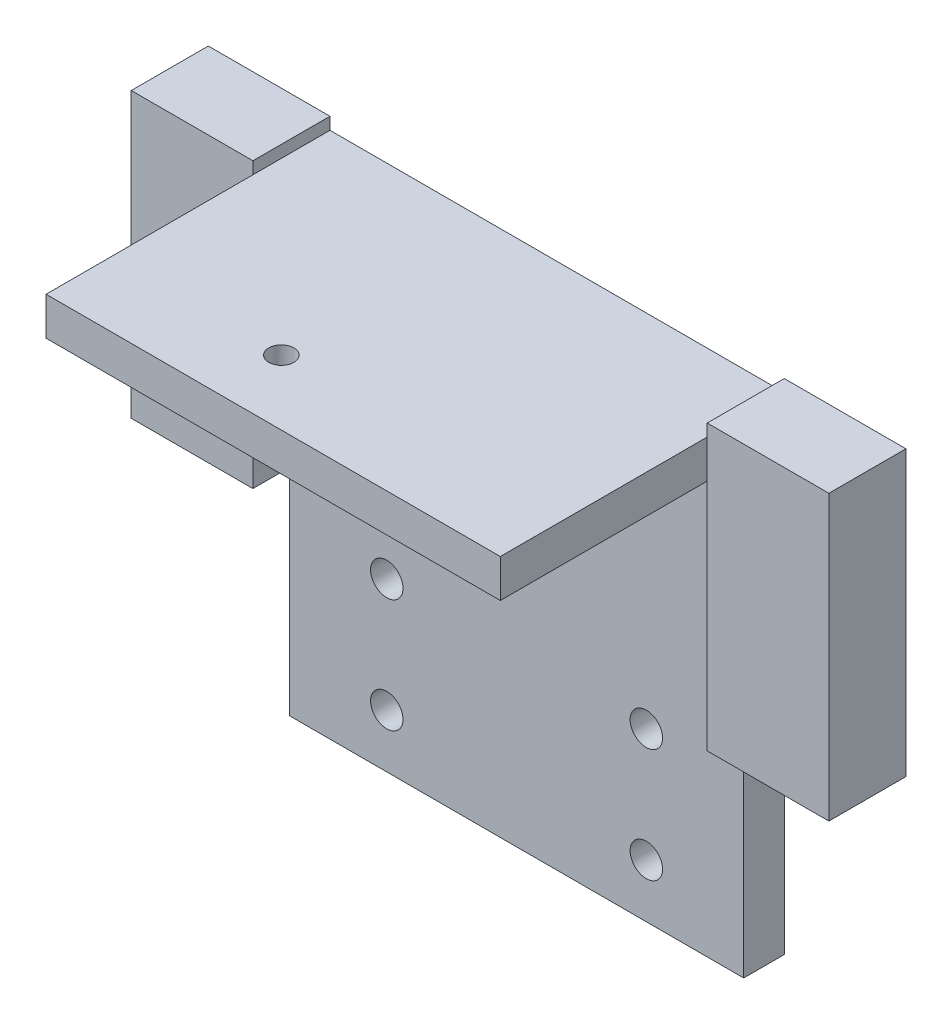
SolidWorks part; units mm, degrees
ref_plane "前视基准面" through (0, 0, 0) normal (0, 0, 1) x (1, 0, 0)
ref_plane "上视基准面" through (0, 0, 0) normal (0, 1, 0) x (1, 0, 0)
ref_plane "右视基准面" through (0, 0, 0) normal (1, 0, 0) x (0, 0, -1)
other "Configuration Table"
sketch "草图1" plane through (0, 0, 0) normal (0, 0, 1) x (1, 0, 0)
  line L1 (-28, -30) -> (28, -30)
  line L2 (-28, -30) -> (-28, 30)
  line L3 (-28, 30) -> (28, 30)
  line L4 (28, -30) -> (28, 30)
  line L5 (-28, -30) -> (28, 30) construction
  line L6 (-28, 30) -> (28, -30) construction
  point P0 (0, 0)
  dimension "D1" = 56
  dimension "D2" = 60
extrude "凸台-拉伸1" add sketch "草图1" along normal blind 5
sketch "草图2" plane through (0, 0, 5) normal (0, 0, 1) x (1, 0, 0)
  line L0 (-16, -23.4) -> (-16, -9.4) construction
  line L1 (-28, -30) -> (28, -30) construction
  line L2 (-28, 30) -> (-28, -30) construction
  circle A0 centre (-16, -23.4) radius 2
  circle A1 centre (-16, -9.4) radius 2
  dimension "D3" = 4
  dimension "D1" = 14
  dimension "D2" = 6.6
  dimension "D4" = 12
extrude "切除-拉伸1" cut sketch "草图2" against normal blind 5
mirror "镜向1" about plane through (0, 0, 0) normal (1, 0, 0) of "切除-拉伸1"
sketch "草图3" plane through (0, 0, 5) normal (0, 0, 1) x (1, 0, 0)
  line L0 (28, -30) -> (28, 30) construction
  line L1 (-28, 30) -> (28, 30)
  line L2 (-28, 30) -> (-28, 25.3)
  line L3 (-28, 25.3) -> (28, 25.3)
  line L4 (28, 30) -> (28, 25.3)
  dimension "D1" = 4.7
extrude "凸台-拉伸2" add sketch "草图3" along normal blind 30
sketch "草图4" plane through (0, 30, 0) normal (0, 1, 0) x (1, 0, 0)
  line L0 (28, 0) -> (-28, 0) construction
  line L1 (-28, -35) -> (-28, 0) construction
  circle A0 centre (-7, -27) radius 1.55
  dimension "D3" = 3.1
  dimension "D1" = 27
  dimension "D2" = 21
extrude "切除-拉伸2" cut sketch "草图4" against normal blind 40
sketch "草图5" plane through (0, 0, 5) normal (0, 0, 1) x (1, 0, 0)
  line L1 (-28, 25.3) -> (-3, 25.3)
  line L2 (-28, 25.3) -> (-28, 1.3)
  line L3 (-28, 1.3) -> (-3, 1.3)
  line L4 (-3, 25.3) -> (-3, 1.3)
  dimension "D1" = 24
  dimension "D2" = 25
extrude "凸台-拉伸3" add sketch "草图5" along normal blind 4.3
sketch "草图6" plane through (-28, 0, 0) normal (-1, 0, 0) x (0, 0, 1)
  line L0 (0, 26.5) -> (0, -3.5)
  line L1 (0, 30) -> (0, -30) construction
  line L8 (0, -3.5) -> (9.5, -3.5)
  line L9 (9.5, -3.5) -> (9.5, 31.5)
  line L10 (9.5, 31.5) -> (0, 31.5)
  line L11 (0, 31.5) -> (0, 26.5)
  point P11 (0, 0)
  dimension "D1" = 30
  dimension "D2" = 35
  dimension "D3" = 9.5
  dimension "D4" = 3.5
extrude "凸台-拉伸4" add sketch "草图6" along normal blind 15
mirror "镜向2" about plane through (0, 0, 0) normal (1, 0, 0) of "凸台-拉伸4"
sketch "草图8" plane through (0, 25.3, 0) normal (0, -1, 0) x (1, 0, 0)
  line L1 (-24.9875, 12.3) -> (24.9875, 12.3) construction
  line L2 (-24.9875, 12.3) -> (-24.9875, 31.3) construction
  line L3 (-24.9875, 31.3) -> (24.9875, 31.3) construction
  line L4 (24.9875, 12.3) -> (24.9875, 31.3) construction
  line L5 (-24.9875, 12.3) -> (24.9875, 31.3) construction
  line L6 (-24.9875, 31.3) -> (24.9875, 12.3) construction
  line L7 (-28, 9.3) -> (-3, 9.3) construction
  line L8 (-28, 35) -> (28, 35) construction
  circle A0 centre (-24.9875, 31.3) radius 1.6
  circle A1 centre (24.9875, 31.3) radius 1.6
  circle A2 centre (24.9875, 12.3) radius 1.6
  circle A3 centre (-24.9875, 12.3) radius 1.6
  point P0 (0, 21.8)
  point P5 (25, 31.3)
  point P6 (0, 21.8)
  point P16 (-24.9875, 31.3)
  dimension "D5" = 3.2
  dimension "D1" = 21.8
  dimension "D2" = 3
  dimension "D4" = 3.7
sketch "草图9" plane through (0, 0, 9.5) normal (0, 0, 1) x (1, 0, 0)
  line L0 (-43, 14) -> (-28, 14) construction
  line L1 (-43, -3.5) -> (-43, 31.5) construction
  line L2 (-28, 25.3) -> (-28, 1.3) construction
  line L3 (-35.5, 14) -> (-35.5, 27.8573) construction
  circle A0 centre (-35.5, 27.8573) radius 2
  circle A1 centre (-35.5, 0.1427) radius 2
  dimension "D1" = 4
